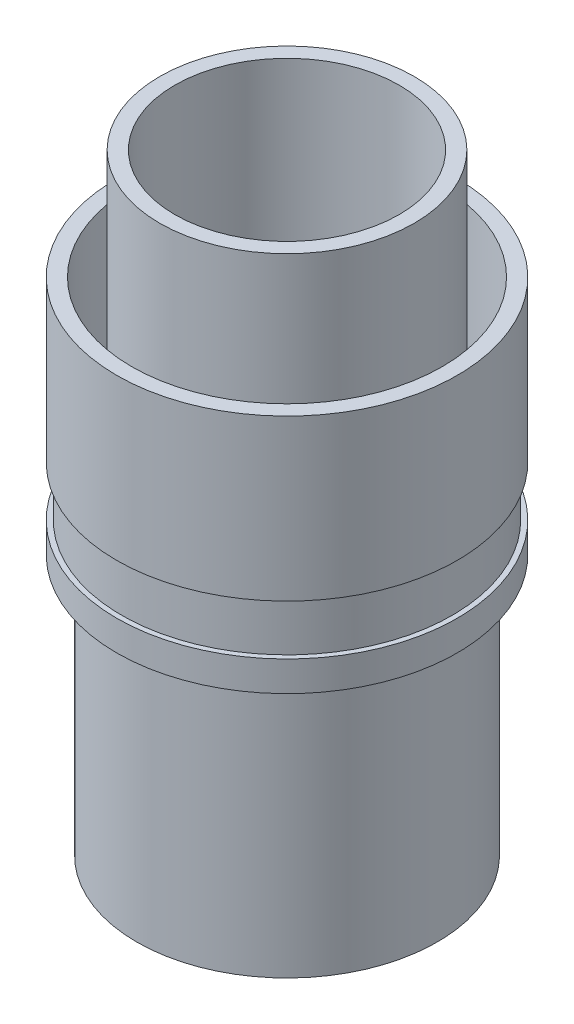
SolidWorks part; units mm, degrees
ref_plane "Ön Düzlem" through (0, 0, 0) normal (0, 0, 1) x (1, 0, 0)
ref_plane "Üst Düzlem" through (0, 0, 0) normal (0, 1, 0) x (1, 0, 0)
ref_plane "Sağ Düzlem" through (0, 0, 0) normal (1, 0, 0) x (0, 0, -1)
sketch "Çizim1" plane through (0, 0, 0) normal (0, 0, 1) x (1, 0, 0)
  line L0 (-20.9122, -5.4369) -> (-20.9122, 55.5631)
  line L1 (-20.9122, 55.5631) -> (-33.6122, 55.5631)
  line L2 (-33.6122, 55.5631) -> (-33.6122, 44.5631)
  line L3 (-33.6122, 44.5631) -> (-37.9122, 44.5631)
  line L4 (-37.9122, 44.5631) -> (-37.9122, 28.5631)
  line L5 (-37.9122, 20.5631) -> (-35.9122, 20.5631)
  line L6 (-35.9122, 20.5631) -> (-35.9122, -5.4369)
  line L7 (-35.9122, -5.4369) -> (-20.9122, -5.4369)
  line L8 (-37.9122, 23.5631) -> (-37.4122, 23.5631)
  line L9 (-37.4122, 23.5631) -> (-37.4122, 28.5631)
  line L10 (-37.4122, 28.5631) -> (-37.9122, 28.5631)
  line L11 (-37.9122, 23.5631) -> (-37.9122, 20.5631)
  dimension "D1" = 24
  dimension "D2" = 15
  dimension "D3" = 17
  dimension "D4" = 12.7
  dimension "D5" = 26
  dimension "D6" = 11
  dimension "D7" = 5
  dimension "D8" = 3
  dimension "D9" = 0.5
revolve "Döndür1" add sketch "Çizim1" angle 360 about L0
sketch "Çizim2" plane through (0, 55.5631, 0) normal (0, 1, 0) x (1, 0, 0)
  circle A0 centre (-20.9122, 0) radius 11.2
  circle A1 centre (-20.9122, 0) radius 15.5
  circle A2 centre (-20.9122, 0) radius 17 construction
  circle A3 centre (-20.9122, 0) radius 12.7 construction
  circle A4 centre (-20.9122, 0) radius 17
  circle A5 centre (-20.9122, 0) radius 12.7
  circle M1 centre (-20.9122, 0) radius 12.7
  dimension "D1" = 1.5
  dimension "D2" = 1.5
extrude "Kes-Ekstrüzyon1" cut sketch "Çizim2" against normal blind 30 contours A0 | A1 M1
sketch "Çizim3" plane through (0, -5.4369, 0) normal (0, -1, 0) x (1, 0, 0)
  circle A0 centre (-20.9122, 0) radius 13.5
  circle A1 centre (-20.9122, 0) radius 15 construction
  dimension "D1" = 1.5
extrude "Kes-Ekstrüzyon2" cut sketch "Çizim3" against normal blind 30
